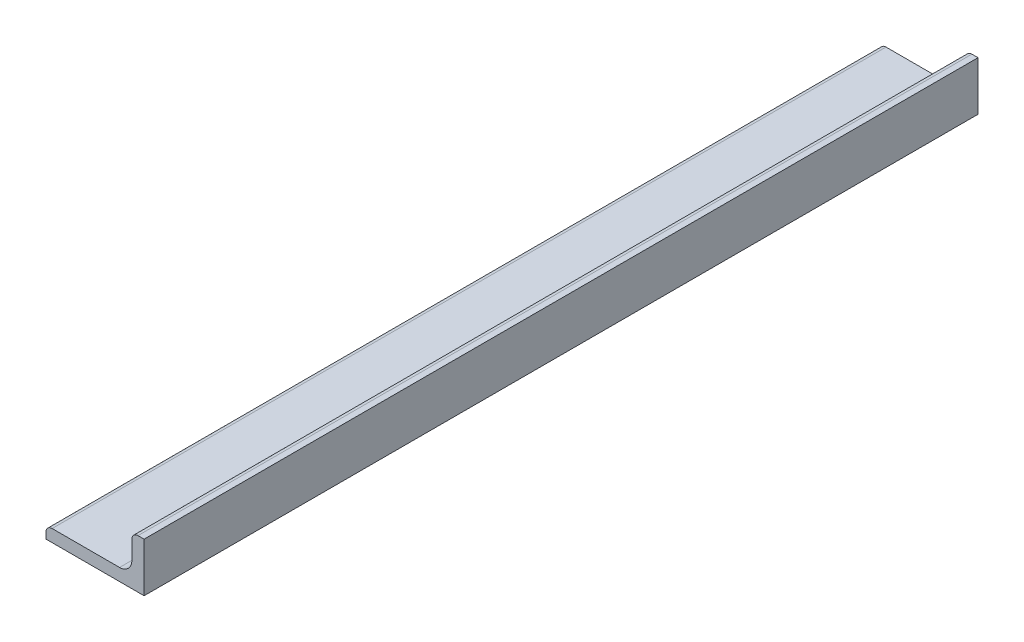
SolidWorks part; units mm, degrees
ref_plane "Front Plane" through (0, 0, 0) normal (0, 0, 1) x (1, 0, 0)
ref_plane "Top Plane" through (0, 0, 0) normal (0, 1, 0) x (1, 0, 0)
ref_plane "Right Plane" through (0, 0, 0) normal (1, 0, 0) x (0, 0, -1)
sketch "Sketch2" plane through (0, 0, 0) normal (0, 0, 1) x (1, 0, 0)
  line L0 (-12.7, 0) -> (12.7, 0)
  line L1 (12.7, 0) -> (12.7, 12.7)
  line L2 (12.7, 12.7) -> (9.525, 12.7) construction
  line L3 (9.525, 11.1125) -> (9.525, 6.35)
  line L4 (6.35, 3.175) -> (-11.1125, 3.175)
  line L5 (-12.7, 0) -> (-12.7, 3.175) construction
  line L6 (11.1125, 12.7) -> (12.7, 12.7)
  line L7 (-12.7, 1.5875) -> (-12.7, 0)
  arc A0 (9.525, 11.1125) -> (11.1125, 12.7) centre (11.1125, 11.1125) cw
  arc A1 (-12.7, 1.5875) -> (-11.1125, 3.175) centre (-11.1125, 1.5875) cw
  arc A2 (9.525, 6.35) -> (6.35, 3.175) centre (6.35, 6.35) cw
  dimension "Inside Radius" = 3.175
  dimension "Vert" = 12.7
  dimension "Horz" = 25.4
  dimension "Thickness" = 3.175
extrude "Boss-Extrude1" add sketch "Sketch2" along normal mid plane 215.9
sketch "Break Locations" plane through (0, 0, 0) normal (1, 0, 0) x (0, 0, -1)
  line L1 (-107.95, 0) -> (-107.95, 12.7) construction
  line L2 (107.95, 0) -> (107.95, 12.7) construction
  point P0 (-97.155, 0)
  point P1 (97.155, 0)
  dimension "D1" = 10.795
  dimension "D2" = 10.795
ref_plane "Contact Plane 1" through (0, 3.175, 0) normal (0, 1, 0) x (1, 0, 0)
ref_plane "Contact Plane 2" through (9.525, 0, 0) normal (-1, 0, 0) x (0, 0, 1)
equation "\"D1@Break Locations\"=.85*\"Vert@Sketch2\""
equation "\"D2@Break Locations\"=\"D1@Break Locations\""
